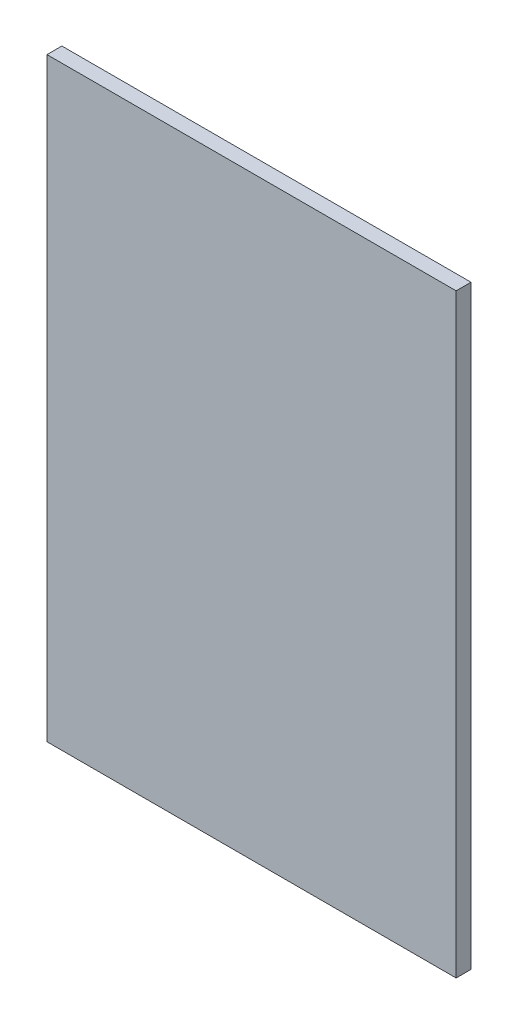
SolidWorks part; units mm, degrees
ref_plane "Plan de face" through (0, 0, 0) normal (0, 0, 1) x (1, 0, 0)
ref_plane "Plan de dessus" through (0, 0, 0) normal (0, 1, 0) x (1, 0, 0)
ref_plane "Plan de droite" through (0, 0, 0) normal (1, 0, 0) x (0, 0, -1)
sketch "Esquisse1" plane through (0, 0, 0) normal (0, 0, 1) x (1, 0, 0)
  line L1 (0, 0) -> (-165, 0)
  line L2 (0, 0) -> (0, 240)
  line L3 (0, 240) -> (-165, 240)
  line L4 (-165, 0) -> (-165, 240)
  dimension "D1" = 240
  dimension "D2" = 165
extrude "Boss.-Extru.1" add sketch "Esquisse1" along normal blind 6
